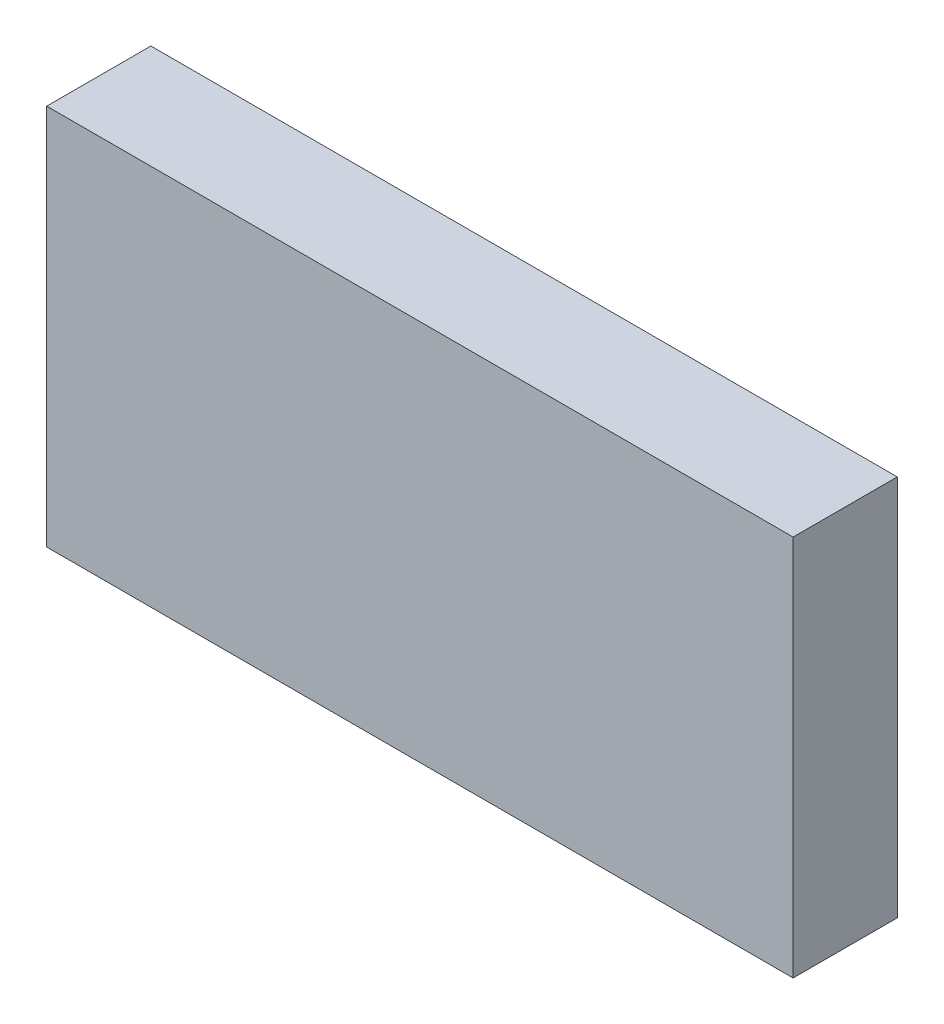
SolidWorks part; units mm, degrees
ref_plane "Front Plane" through (0, 0, 0) normal (0, 0, 1) x (1, 0, 0)
ref_plane "Top Plane" through (0, 0, 0) normal (0, 1, 0) x (1, 0, 0)
ref_plane "Right Plane" through (0, 0, 0) normal (1, 0, 0) x (0, 0, -1)
sketch "Sketch2" plane through (0, 0, 0) normal (0, 1, 0) x (1, 0, 0)
  line L1 (-107.5, 15) -> (107.5, 15)
  line L2 (-107.5, 15) -> (-107.5, -15)
  line L3 (-107.5, -15) -> (107.5, -15)
  line L4 (107.5, 15) -> (107.5, -15)
  point P4 (129, -52.8968)
  dimension "D1" = 215
  dimension "D2" = 30
  dimension "D3" = 107.5
  dimension "D4" = 15
extrude "Boss-Extrude1" add sketch "Sketch2" along normal blind 110
